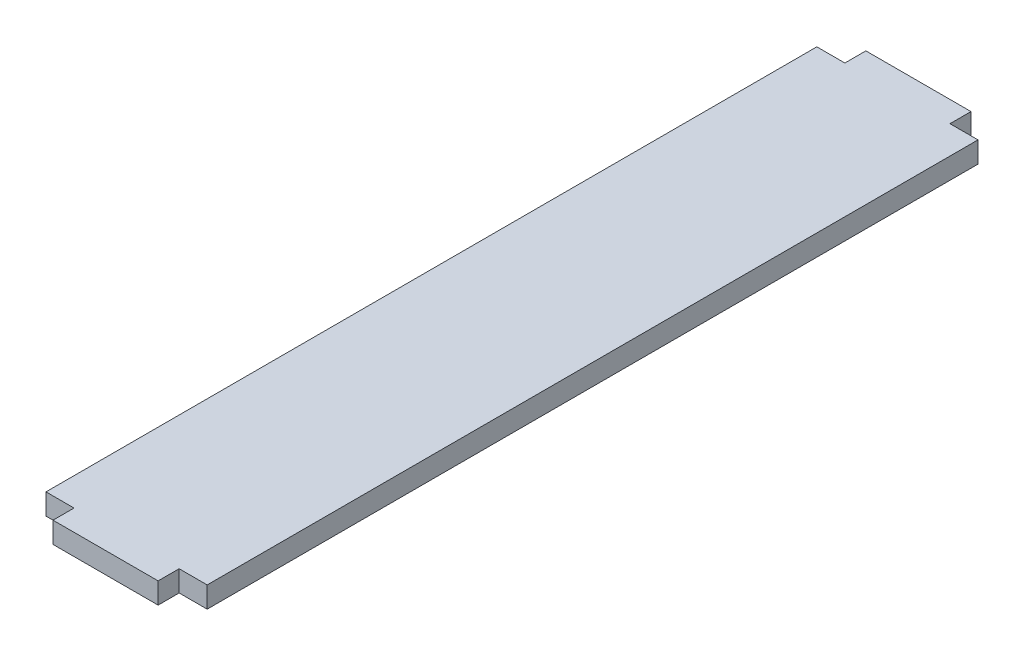
SolidWorks part; units mm, degrees
material "AISI 304"
ref_plane "Front Plane" through (0, 0, 0) normal (0, 0, 1) x (1, 0, 0)
ref_plane "Top Plane" through (0, 0, 0) normal (0, 1, 0) x (1, 0, 0)
ref_plane "Right Plane" through (0, 0, 0) normal (1, 0, 0) x (0, 0, -1)
sketch "Sketch1" plane through (0, 0, 0) normal (0, 1, 0) x (1, 0, 0)
  line L0 (3.75, 27.5) -> (5.75, 27.5)
  line L1 (-5.75, -27.5) -> (-3.75, -27.5)
  line L2 (-5.75, -27.5) -> (-5.75, -19.1)
  line L3 (-5.75, 27.5) -> (-3.75, 27.5)
  line L4 (5.75, -27.5) -> (5.75, -14.1)
  line L5 (-5.75, -27.5) -> (5.75, 27.5) construction
  line L6 (-5.75, 27.5) -> (5.75, -27.5) construction
  line L8 (3.75, 27.5) -> (3.75, 29)
  line L9 (3.75, 29) -> (-3.75, 29)
  line L10 (-3.75, 27.5) -> (-3.75, 29)
  line L12 (-3.75, -27.5) -> (-3.75, -29)
  line L13 (-3.75, -29) -> (3.75, -29)
  line L14 (3.75, -27.5) -> (3.75, -29)
  line L15 (3.75, -27.5) -> (5.75, -27.5)
  line L16 (-5.75, -17.4) -> (-5.75, 27.5)
  line L21 (5.75, -12.4) -> (5.75, 27.5)
  line L26 (-5.75, -19.1) -> (-5.75, -17.4)
  line L27 (5.75, -14.1) -> (5.75, -12.4)
  point P0 (0, 0)
  dimension "D1" = 7.5
  dimension "D2" = 2
  dimension "D3" = 2
  dimension "D4" = 1.5
  dimension "D5" = 2
  dimension "D6" = 2
  dimension "D7" = 1.5
  dimension "D8" = 55
extrude "Boss-Extrude1" add sketch "Sketch1" along normal blind 1.5
